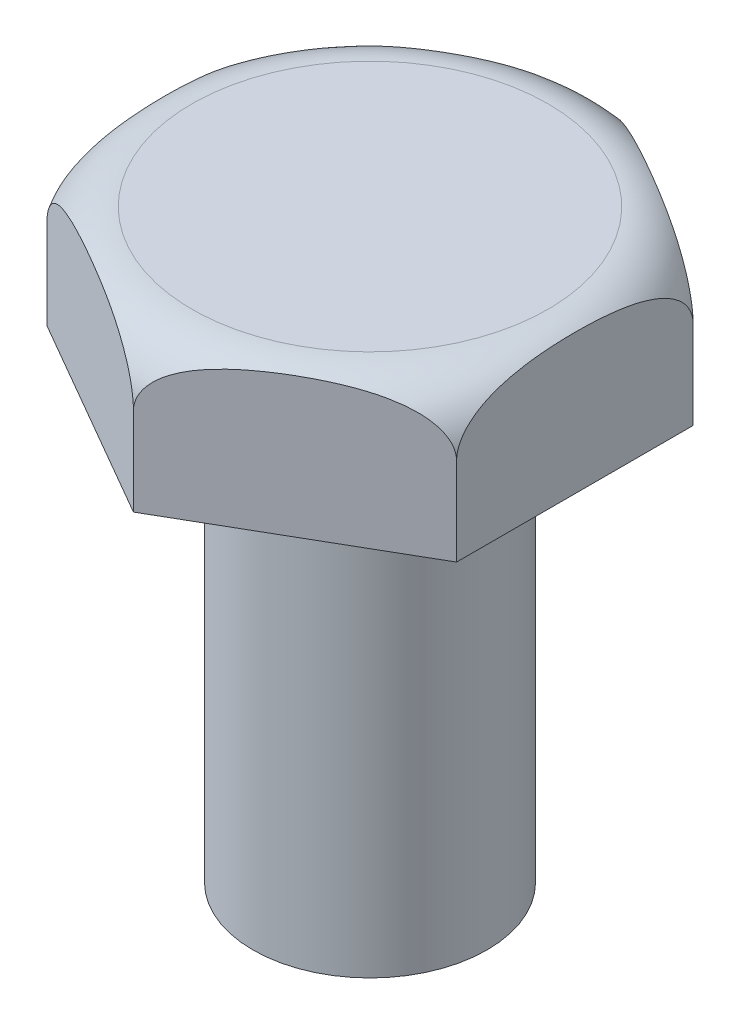
SolidWorks part; units mm, degrees
ref_plane "Front Plane" through (0, 0, 0) normal (0, 0, 1) x (1, 0, 0)
ref_plane "Top Plane" through (0, 0, 0) normal (0, 1, 0) x (1, 0, 0)
ref_plane "Right Plane" through (0, 0, 0) normal (1, 0, 0) x (0, 0, -1)
sketch "Sketch1" plane through (0, 0, 0) normal (0, 1, 0) x (1, 0, 0)
  circle A0 centre (0, 0) radius 4
  dimension "D1" = 8
extrude "Boss-Extrude1" add sketch "Sketch1" along normal blind 15
sketch "Sketch2" plane through (0, 15, 0) normal (0, 1, 0) x (1, 0, 0)
  line L1 (0, -8.0829) -> (7, -4.0415)
  line L2 (7, -4.0415) -> (7, 4.0415)
  line L3 (7, 4.0415) -> (0, 8.0829)
  line L4 (0, 8.0829) -> (-7, 4.0415)
  line L5 (-7, 4.0415) -> (-7, -4.0415)
  line L6 (-7, -4.0415) -> (0, -8.0829)
  circle A0 centre (0, 0) radius 7 construction
  dimension "D1" = 14
extrude "Boss-Extrude2" add sketch "Sketch2" along normal blind 5
sketch "Sketch4" plane through (0, 0, 0) normal (1, 0, 0) x (0, 0, -1)
  line L0 (0, 0) -> (0, 25.896) construction
  line L5 (-4.0415, 20) -> (-8.0829, 20) construction
  line L6 (-8.0829, 20) -> (-8.0829, 15) construction
  line L7 (-6.0829, 20) -> (-8.0829, 20)
  line L8 (-8.0829, 20) -> (-8.0829, 18)
  arc A1 (-6.0829, 20) -> (-8.0829, 18) centre (-6.0829, 18) ccw
  dimension "D1" = 2
revolve "Cut-Revolve2" cut sketch "Sketch4" angle 360 about L0
